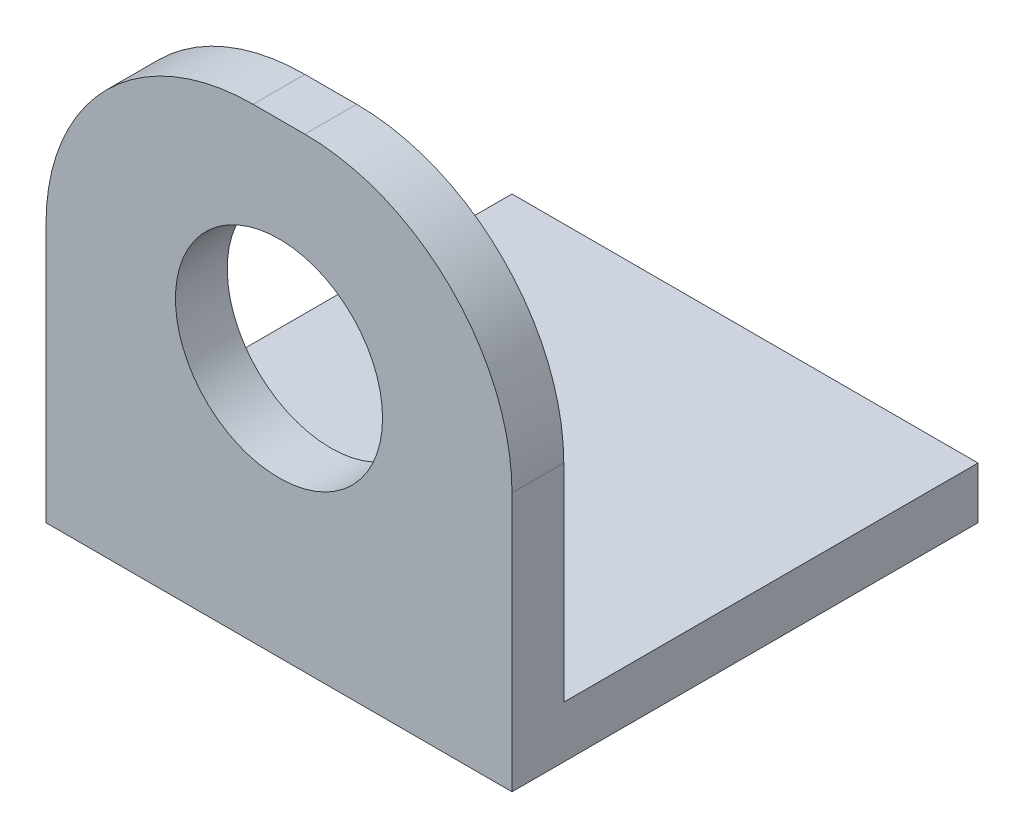
SolidWorks part; units mm, degrees
material "1060 Alloy"
ref_plane "Front Plane" through (0, 0, 0) normal (0, 0, 1) x (1, 0, 0)
ref_plane "Top Plane" through (0, 0, 0) normal (0, 1, 0) x (1, 0, 0)
ref_plane "Right Plane" through (0, 0, 0) normal (1, 0, 0) x (0, 0, -1)
sketch "Sketch1" plane through (0, 0, 0) normal (1, 0, 0) x (0, 0, -1)
  line L0 (-1, 8) -> (-1, -1)
  line L1 (-1, -1) -> (8, -1)
  line L2 (8, -1) -> (8, 0)
  line L3 (8, 0) -> (0, 0)
  line L4 (0, 0) -> (0, 8)
  line L5 (0, 8) -> (-1, 8)
  line L6 (0, 5) -> (0, 3) construction
  point P9 (0, 0.4487)
  point P10 (0, 3.2179)
  point P11 (0, 4.2094)
  point P12 (0, 5.04)
  point P13 (0, 4)
  point P14 (0, 4)
  point P15 (4.3679, 0)
  point P16 (0, 4)
  point P17 (5.3261, 0)
  dimension "D1" = 1
  dimension "D2" = 2
  dimension "D3" = 9
  dimension "D4" = 9
extrude "Boss-Extrude1" add sketch "Sketch1" along normal blind 9
sketch "Sketch2" plane through (0, 0, 1) normal (0, 0, 1) x (1, 0, 0)
  line L4 (0, 8) -> (0, -1)
  line L5 (0, -1) -> (9, -1)
  line L6 (9, -1) -> (9, 8)
  line L7 (9, 8) -> (0, 8)
  line L8 (0, 8) -> (0, -1) construction
  line L9 (0, -1) -> (9, -1) construction
  line L10 (9, -1) -> (9, 8) construction
  line L11 (9, 8) -> (0, 8) construction
  circle A0 centre (4.5, 4) radius 2
  point P2 (0, 0)
  point P5 (4.5, 8)
  dimension "D2" = 4
  dimension "D1" = 0
extrude "Cut-Extrude1" cut sketch "Sketch2" against normal blind 10
fillet "Fillet1" radius 4 2 edges at (0, 8, 0.5) (9, 8, 0.5)
